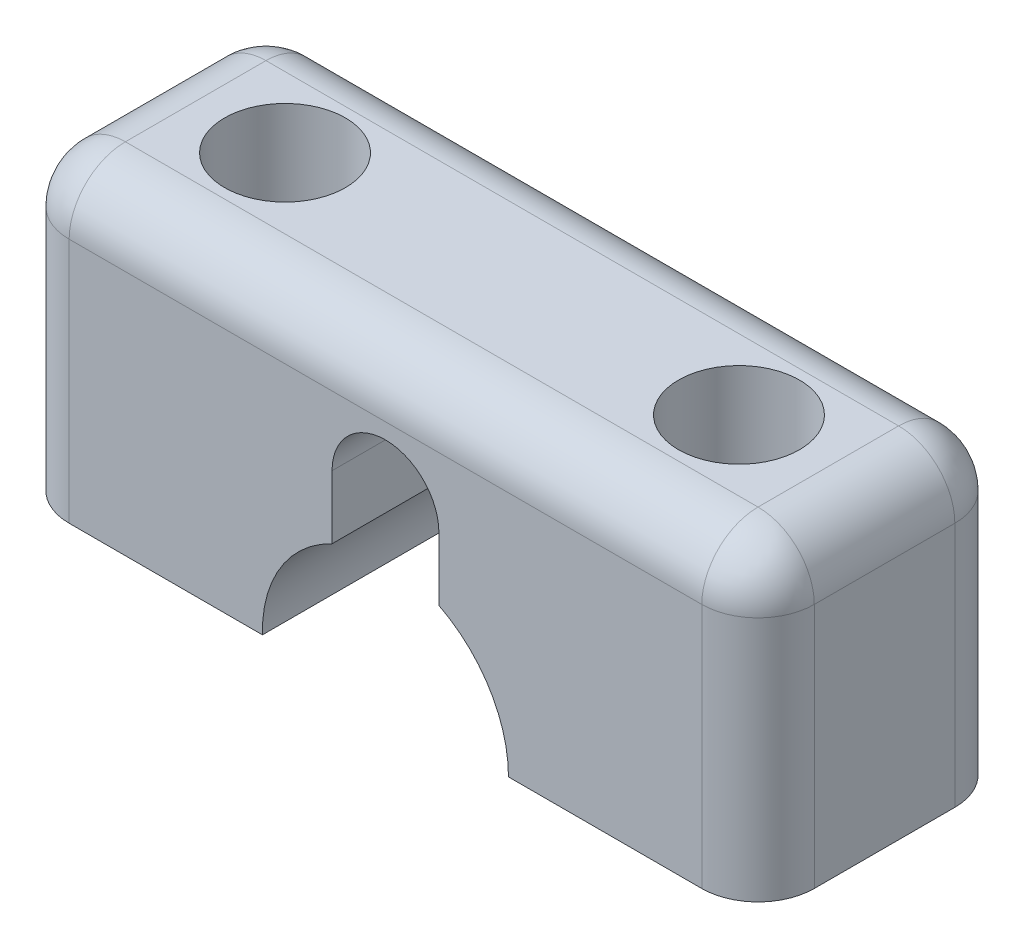
SolidWorks part; units mm, degrees
ref_plane "Front Plane" through (0, 0, 0) normal (0, 0, 1) x (1, 0, 0)
ref_plane "Top Plane" through (0, 0, 0) normal (0, 1, 0) x (1, 0, 0)
ref_plane "Right Plane" through (0, 0, 0) normal (1, 0, 0) x (0, 0, -1)
sketch "Sketch4" plane through (0, 0, 0) normal (0, 0, 1) x (1, 0, 0)
  line L0 (1168.1756, 117.6995) -> (1168.1756, 467.6995)
  line L1 (1088.1756, 547.6995) -> (188.1756, 547.6995)
  line L2 (108.1756, 467.6995) -> (108.1756, 117.6995)
  line L3 (108.1756, 117.6995) -> (1168.1756, 117.6995)
  line L4 (638.1756, 117.6995) -> (638.1756, 576.7142) construction
  line L5 (562.1756, 279.458) -> (562.1756, 369.458)
  line L6 (714.1756, 279.458) -> (714.1756, 369.458)
  arc A0 (1168.1756, 467.6995) -> (1088.1756, 547.6995) centre (1088.1756, 467.6995) ccw
  arc A1 (188.1756, 547.6995) -> (108.1756, 467.6995) centre (188.1756, 467.6995) ccw
  arc A2 (562.1756, 279.458) -> (463.1756, 117.6995) centre (637.1115, 122.421) ccw
  arc A3 (562.1756, 369.458) -> (714.1756, 369.458) centre (638.1756, 369.458) cw
  arc A4 (714.1756, 279.458) -> (813.1756, 117.6995) centre (639.2397, 122.421) cw
  dimension "D2" = 80
  dimension "D5" = 80
  dimension "D6" = 174
  dimension "D8" = 76
  dimension "D1" = 900
  dimension "D3" = 350
  dimension "D4" = 355
  dimension "D7" = 90
sketch "Sketch5" plane through (0, 0, 0) normal (0, 1, 0) x (1, 0, 0)
  line L0 (263.6761, -71.8222) -> (1419.6761, -71.8222) construction
sketch "Sketch6" plane through (0, 0, 0) normal (0, 1, 0) x (1, 0, 0)
  line L0 (115.4795, 99.0286) -> (115.4795, -99.0286)
  line L1 (108.1756, 0) -> (188.1756, 0) construction
  line L2 (195.4795, -179.0286) -> (1095.4795, -179.0286)
  line L3 (1163.0507, 100) -> (1163.0507, -100)
  line L4 (1088.1756, 0) -> (1168.1756, 0) construction
  line L5 (108.1756, 0) -> (1168.1756, 0) construction
  line L6 (74.9008, 0) -> (1270.1389, 0) construction
  line L7 (195.4795, 179.0286) -> (1095.4795, 179.0286)
  arc A0 (115.4795, -99.0286) -> (195.4795, -179.0286) centre (195.4795, -99.0286) ccw
  arc A1 (1163.0507, -100) -> (1095.4795, -179.0286) centre (1083.0507, -100) cw
  arc A2 (115.4795, 99.0286) -> (195.4795, 179.0286) centre (195.4795, 99.0286) cw
  arc A3 (1163.0507, 100) -> (1095.4795, 179.0286) centre (1083.0507, 100) ccw
  circle A4 centre (961.1004, 0) radius 52.5
  circle A5 centre (961.1004, 0) radius 105
  point P6 (115.4795, 0)
  point P23 (1163.0507, 0)
  dimension "D2" = 80
  dimension "D4" = 80
  dimension "D5" = 105
  dimension "D6" = 210
  dimension "D1" = 900
  dimension "D3" = 200
extrude "Boss-Extrude2" add sketch "Sketch4" along normal mid plane 200 contours L4 A3 L6 A4 L3 L0 A0 L1 | A3 L4 L1 A1 L2 L3 A2 L5
sketch "Sketch7" plane through (0, 0, -100) normal (0, 0, -1) x (-1, 0, 0)
  line L0 (-1088.1756, 547.6995) -> (-1088.1756, 117.6995)
  line L1 (-813.1756, 117.6995) -> (-1168.1756, 117.6995) construction
  line L2 (-1088.1756, 117.6995) -> (-1168.1756, 117.6995)
  line L3 (-1168.1756, 117.6995) -> (-1168.1756, 467.6995)
  arc A0 (-1168.1756, 467.6995) -> (-1088.1756, 547.6995) centre (-1088.1756, 467.6995) cw
revolve "Revolve1" add sketch "Sketch7" angle 90 about L0
sketch "Sketch8" plane through (0, 0, -100) normal (0, 0, -1) x (-1, 0, 0)
  line L0 (-188.1756, 547.6995) -> (-188.1756, 117.6995)
  line L1 (-108.1756, 117.6995) -> (-463.1756, 117.6995) construction
  line L2 (-188.1756, 117.6995) -> (-108.1756, 117.6995)
  line L3 (-108.1756, 117.6995) -> (-108.1756, 467.6995)
  arc A0 (-108.1756, 467.6995) -> (-188.1756, 547.6995) centre (-188.1756, 467.6995) ccw
revolve "Revolve2" add sketch "Sketch8" angle 90 about L0
sketch "Sketch9" plane through (0, 0, -100) normal (0, 0, -1) x (-1, 0, 0)
  line L0 (-1088.1756, 547.6995) -> (-1088.1756, 117.6995)
  line L1 (-1088.1756, 117.6995) -> (-813.1756, 117.6995)
  line L2 (-714.1756, 279.458) -> (-714.1756, 369.458)
  line L3 (-562.1756, 369.458) -> (-562.1756, 279.458)
  line L4 (-463.1756, 117.6995) -> (-188.1756, 117.6995)
  line L5 (-188.1756, 117.6995) -> (-188.1756, 547.6995)
  line L6 (-188.1756, 547.6995) -> (-1088.1756, 547.6995)
  line L7 (-813.1756, 117.6995) -> (-463.1756, 117.6995)
  arc A0 (-813.1756, 117.6995) -> (-714.1756, 279.458) centre (-631.525, 117.6995) cw
  arc A1 (-714.1756, 369.458) -> (-562.1756, 369.458) centre (-638.1756, 369.458) cw
  arc A2 (-562.1756, 279.458) -> (-463.1756, 117.6995) centre (-637.1115, 122.421) cw
sketch "Sketch10" plane through (1088.1756, 0, 0) normal (-1, 0, 0) x (0, 0, 1)
  line L0 (-100, 547.6995) -> (-100, 467.6995)
  line L1 (-100, 117.6995) -> (-100, 547.6995) construction
  line L2 (-100, 467.6995) -> (-180, 467.6995)
  line L3 (-180, 467.6995) -> (-180, 117.6995)
  line L4 (-180, 117.6995) -> (-100, 117.6995)
  line L5 (-100, 117.6995) -> (-100, 467.6995)
  arc A0 (-180, 467.6995) -> (-100, 547.6995) centre (-100, 467.6995) cw
  arc M1 (-100, 547.6995) -> (-180, 467.6995) centre (-100, 467.6995) ccw
  line M2 (-180, 467.6995) -> (-180, 117.6995)
  line M3 (-180, 117.6995) -> (-100, 117.6995)
  line M4 (-100, 117.6995) -> (-100, 547.6995)
extrude "Boss-Extrude3" add sketch "Sketch10" along normal up to surface (900 mm away) contours L2 M4 M1 | L2 M4 M2 M3 up to face at (188.1756, 316.8416, -144.1421)
sketch "Sketch11" plane through (0, 0, 100) normal (0, 0, 1) x (1, 0, 0)
  line L0 (1088.1756, 547.6995) -> (1088.1756, 117.6995)
  line L1 (1088.1756, 117.6995) -> (1168.1756, 117.6995)
  line L2 (1168.1756, 117.6995) -> (1168.1756, 467.6995)
  arc A0 (1168.1756, 467.6995) -> (1088.1756, 547.6995) centre (1088.1756, 467.6995) ccw
revolve "Revolve3" add sketch "Sketch11" angle 90 about L0
sketch "Sketch12" plane through (0, 0, 100) normal (0, 0, 1) x (1, 0, 0)
  line L0 (188.1756, 547.6995) -> (188.1756, 117.6995)
  line L1 (188.1756, 117.6995) -> (108.1756, 117.6995)
  line L2 (108.1756, 117.6995) -> (108.1756, 467.6995)
  arc A0 (108.1756, 467.6995) -> (188.1756, 547.6995) centre (188.1756, 467.6995) cw
revolve "Revolve4" add sketch "Sketch12" angle 90 about L0
sketch "Sketch13" plane through (188.1756, 0, 0) normal (1, 0, 0) x (0, 0, -1)
  line L0 (-100, 547.6995) -> (-100, 117.6995)
  line L1 (-100, 117.6995) -> (-180, 117.6995)
  line L2 (-180, 117.6995) -> (-180, 467.6995)
  arc A0 (-180, 467.6995) -> (-100, 547.6995) centre (-100, 467.6995) cw
extrude "Boss-Extrude4" add sketch "Sketch13" along normal up to surface (900 mm away) up to face at (1088.1756, 316.8416, 144.1421)
sketch "Sketch14" plane through (0, 547.6995, 0) normal (0, 1, 0) x (1, 0, 0)
  line L0 (638.1756, -213.7123) -> (638.1756, 281.8841) construction
  circle A0 centre (961.1004, 0) radius 43
  circle A1 centre (961.1004, 0) radius 86
  circle A2 centre (315.2508, 0) radius 86
  circle A3 centre (315.2508, 0) radius 43
  dimension "D1" = 172
  dimension "D2" = 86
extrude "Cut-Extrude2" cut sketch "Sketch14" against normal blind 135
sketch "Sketch17" plane through (0, 547.6995, 0) normal (0, 1, 0) x (1, 0, 0)
  circle A0 centre (961.1004, 0) radius 43
  circle A1 centre (315.2508, 0) radius 43
extrude "Cut-Extrude3" cut sketch "Sketch17" against normal blind 583
sketch "Sketch18" plane through (0, 0, -180) normal (0, 0, -1) x (-1, 0, 0)
  line L0 (-714.1756, 279.458) -> (-714.1756, 369.458)
  line L1 (-562.1756, 369.458) -> (-562.1756, 279.458)
  line L2 (-813.1756, 117.6995) -> (-463.1756, 117.6995)
  arc A0 (-813.1756, 117.6995) -> (-714.1756, 279.458) centre (-631.525, 117.6995) cw
  arc A1 (-714.1756, 369.458) -> (-562.1756, 369.458) centre (-638.1756, 369.458) cw
  arc A2 (-562.1756, 279.458) -> (-463.1756, 117.6995) centre (-637.1115, 122.421) cw
extrude "Cut-Extrude4" cut sketch "Sketch18" against normal through all
